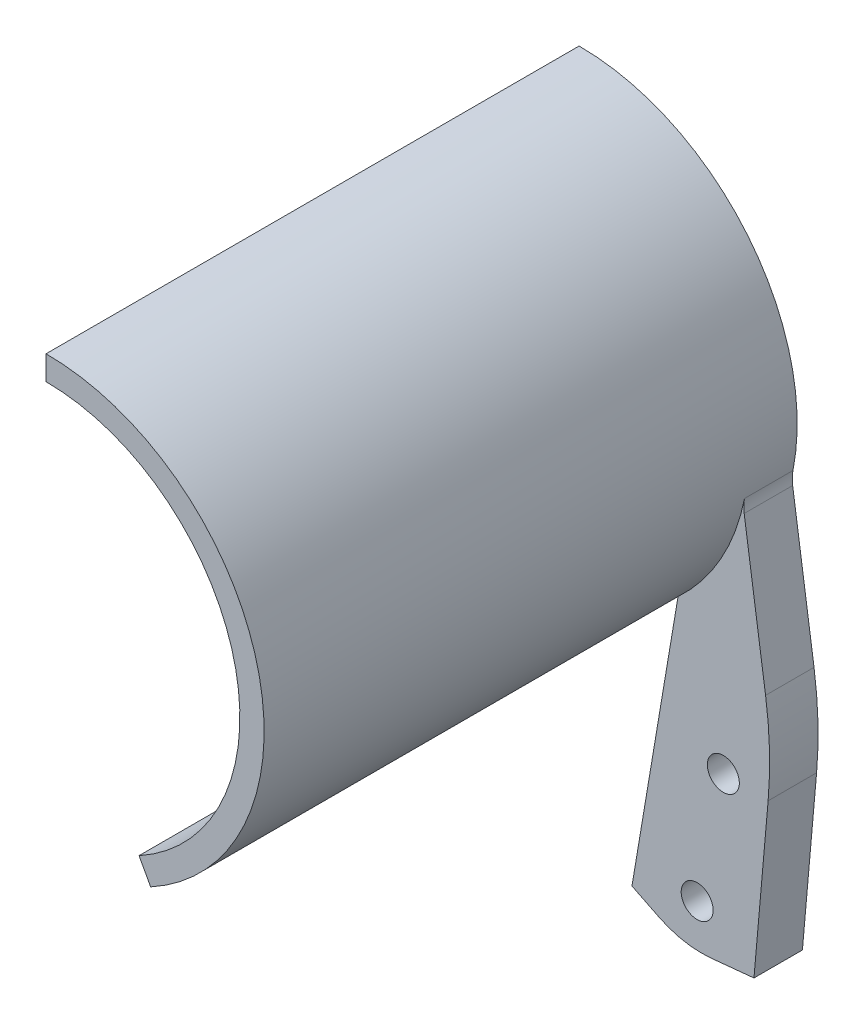
SolidWorks part; units mm, degrees
ref_plane "前视基准面" through (0, 0, 0) normal (0, 0, 1) x (1, 0, 0)
ref_plane "上视基准面" through (0, 0, 0) normal (0, 1, 0) x (1, 0, 0)
ref_plane "右视基准面" through (0, 0, 0) normal (1, 0, 0) x (0, 0, -1)
other "Configuration Table"
sketch "草图1" plane through (0, 0, 0) normal (0, 0, 1) x (1, 0, 0)
  line L5 (0, 0) -> (-23, 0) construction
  line L6 (-11.5, 0) -> (-11.5, 74.1629) construction
  line L9 (-11.5, 79.5) -> (-11.5, 82)
  line L11 (-1.0471, 14.6646) -> (3.7097, 42.9194)
  line L12 (-1.6292, 12.8088) -> (6.0667, 37.3455) construction
  line L13 (-1.0471, 14.6646) -> (4.2787, 12.0253)
  line L14 (4.2787, 12.0253) -> (11.5399, 12.741)
  line L15 (14.2578, 35.2287) -> (10.6514, 5.3898) construction
  line L16 (11.5399, 12.741) -> (13.4146, 33.9693)
  line L17 (13.4146, 33.9693) -> (10.427, 54.4544)
  line L19 (-0.7076, 39.7573) -> (-1.9067, 41.951)
  circle A0 centre (5.6795, 16.6838) radius 1.65 construction
  circle A1 centre (8.3823, 29.3997) radius 1.65 construction
  circle A3 centre (5.6795, 16.6838) radius 1.65
  circle A4 centre (8.3823, 29.3997) radius 1.65
  arc A8 (-1.9067, 41.951) -> (-11.5, 79.5) centre (-11.5, 59.5) ccw
  arc A9 (-0.7076, 39.7573) -> (3.7097, 42.9194) centre (-11.5, 59.5) ccw
  arc A10 (10.427, 54.4544) -> (-11.5, 82) centre (-11.5, 59.5) ccw
  dimension "D1" = 22.5
  dimension "D2" = 59.5
extrude "凸台-拉伸1" add sketch "草图1" along normal blind 5
fillet "圆角2" radius 4 1 edges at (10.427, 54.4544, 2.5)
fillet "圆角3" radius 40 1 edges at (13.4146, 33.9693, 2.5)
fillet "圆角4" radius 10 1 edges at (4.2787, 12.0253, 2.5)
sketch "草图2" plane through (0, 0, 0) normal (0, 0, -1) x (-1, 0, 0)
  line L0 (11.5, 82) -> (11.5, 79.5) construction
  line L2 (11.5, 82) -> (11.5, 79.5)
  line L5 (1.9067, 41.951) -> (0.7076, 39.7573)
  arc A2 (11.5, 79.5) -> (1.9067, 41.951) centre (11.5, 59.5) ccw construction
  arc A4 (11.5, 82) -> (-10.566, 55.1021) centre (11.5, 59.5) ccw construction
  arc A5 (11.5, 79.5) -> (1.9067, 41.951) centre (11.5, 59.5) ccw
  arc A10 (11.5, 82) -> (0.7076, 39.7573) centre (11.5, 59.5) ccw
extrude "凸台-拉伸2" add sketch "草图2" against normal blind 55
